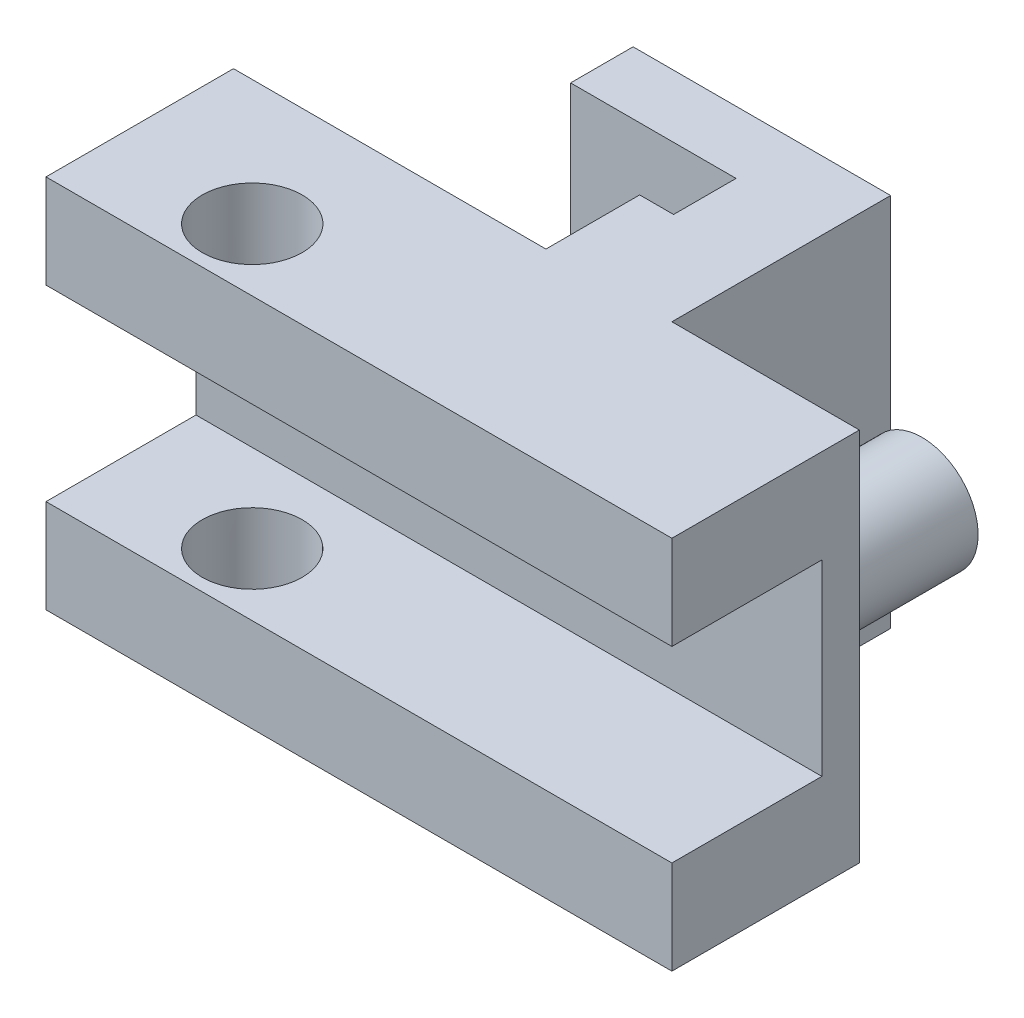
SolidWorks part; units mm, degrees
ref_plane "Front Plane" through (0, 0, 0) normal (0, 0, 1) x (1, 0, 0)
ref_plane "Top Plane" through (0, 0, 0) normal (0, 1, 0) x (1, 0, 0)
ref_plane "Right Plane" through (0, 0, 0) normal (1, 0, 0) x (0, 0, -1)
sketch "Sketch1" plane through (0, 0, 0) normal (0, 1, 0) x (1, 0, 0)
  line L10 (-16.2703, 4.5185) -> (-14.2703, 4.5185)
  line L11 (-14.2703, 4.5185) -> (-14.2703, 5.7685)
  line L12 (-14.2703, 5.7685) -> (-13.999, 5.7685)
  line L13 (-13.999, 5.7685) -> (-13.999, 6.2685)
  line L14 (-13.999, 6.2685) -> (-15.3229, 6.2685)
  line L15 (-15.3229, 6.2685) -> (-15.3229, 6.7685)
  line L16 (-15.3229, 6.7685) -> (-13.2625, 6.7685)
  line L19 (-16.2703, 3.5185) -> (-11.7625, 3.5185)
  line L21 (-16.7703, 4.0185) -> (-15.6203, 4.0185)
  line L22 (-13.2625, 6.7685) -> (-13.2625, 4.5185)
  line L23 (-13.2625, 4.5185) -> (-11.7625, 4.5185)
  line L24 (-11.7625, 4.5185) -> (-11.7625, 3.5185)
  line L25 (-16.2703, 4.5185) -> (-16.7703, 4.5185)
  line L26 (-16.7703, 4.5185) -> (-16.7703, 3.5185)
  line L27 (-16.7703, 3.5185) -> (-16.2703, 3.5185)
  line L28 (-16.7703, 4.5185) -> (-16.7703, 5.0185)
  line L29 (-16.7703, 5.0185) -> (-14.2703, 5.0185)
  line L30 (-13.2625, 5.0185) -> (-11.7625, 5.0185)
  line L31 (-11.7625, 5.0185) -> (-11.7625, 4.5185)
  circle A0 centre (-15.6203, 4.0185) radius 0.4
extrude "Boss-Extrude1" add sketch "Sketch1" along normal blind 3
sketch "Sketch2" plane through (0, 0, -3.5185) normal (0, 0, 1) x (1, 0, 0)
  line L0 (-16.7703, 1.5) -> (-11.7625, 1.5)
  line L1 (-16.7703, 3) -> (-16.7703, 0) construction
  line L2 (-11.7625, 3) -> (-11.7625, 0) construction
  line L3 (-14.2664, 3) -> (-14.2664, 0)
  line L4 (-16.7703, 3) -> (-11.7625, 3) construction
  line L5 (-16.7703, 0) -> (-11.7625, 0) construction
  line L7 (-16.7703, 2.25) -> (-11.7625, 2.25)
  line L8 (-16.7703, 2.25) -> (-16.7703, 0.75)
  line L9 (-16.7703, 0.75) -> (-11.7625, 0.75)
  line L10 (-11.7625, 2.25) -> (-11.7625, 0.75)
  line L11 (-16.7703, 2.25) -> (-11.7625, 0.75) construction
  line L12 (-16.7703, 0.75) -> (-11.7625, 2.25) construction
  point P12 (-14.2664, 1.5)
  line M6 (-11.7625, 0) -> (-11.7625, 3)
  line M8 (-16.7703, 3) -> (-16.7703, 0)
extrude "Cut-Extrude1" cut sketch "Sketch2" against normal blind 1.2 contours L7 L0 L3 M8 | L7 L3 L0 M6 | L9 L3 L0 M8 | L3 L9 L0 M6
sketch "Sketch3" plane through (0, 0, -5.0185) normal (0, 0, -1) x (-1, 0, 0)
  line L0 (12.5125, 3) -> (12.5125, 1.5)
  line L1 (13.2625, 3) -> (11.7625, 3) construction
  circle A0 centre (12.5125, 1.5) radius 0.45
extrude "Boss-Extrude2" add sketch "Sketch3" along normal blind 1.25
